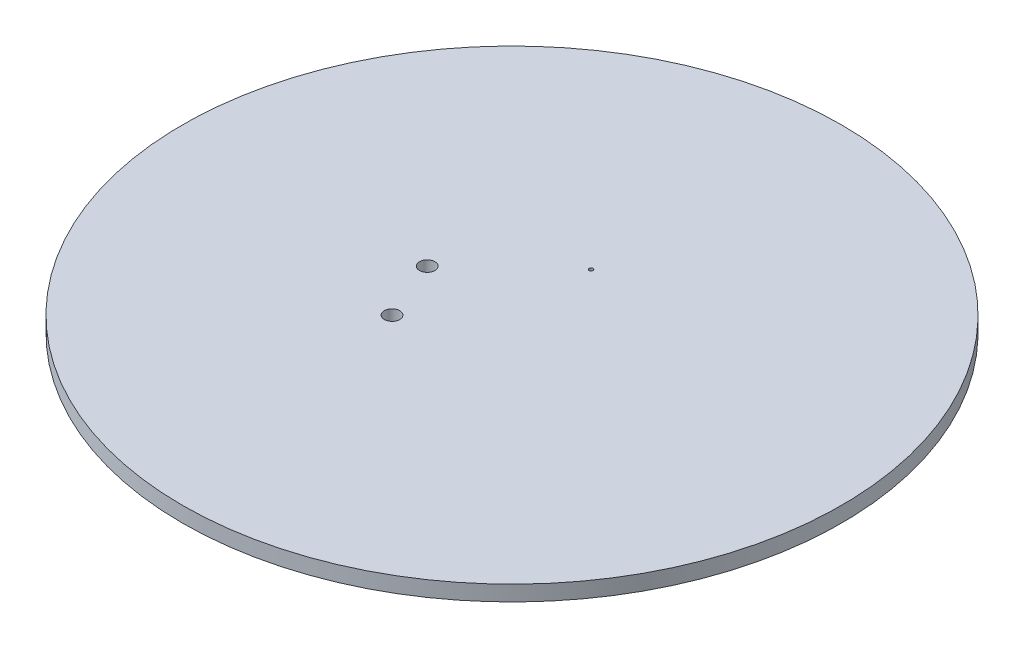
SolidWorks part; units mm, degrees
material "PTFE (general)"
ref_plane "Front Plane" through (0, 0, 0) normal (0, 0, 1) x (1, 0, 0)
ref_plane "Top Plane" through (0, 0, 0) normal (0, 1, 0) x (1, 0, 0)
ref_plane "Right Plane" through (0, 0, 0) normal (1, 0, 0) x (0, 0, -1)
sketch "Sketch1" plane through (0, 0, 0) normal (0, 1, 0) x (1, 0, 0)
  circle A0 centre (0, 0) radius 42.73
  dimension "D2" = 85.46
extrude "Boss-Extrude1" add sketch "Sketch1" along normal blind 2
sketch "Sketch2" plane through (0, 2, 0) normal (0, 1, 0) x (1, 0, 0)
  circle A0 centre (0, 10.25) radius 0.25
  dimension "D1" = 0.5
  dimension "D2" = 10.25
extrude "Cut-Extrude1" cut sketch "Sketch2" against normal through all both and the other way through all
sketch "Sketch3" plane through (0, 2, 0) normal (0, 1, 0) x (1, 0, 0)
  line L0 (0, 0) -> (-36.0536, 0) construction
  line L1 (0, 0) -> (0, 10.25) construction
  line L2 (0, 10.25) -> (0, 0) construction
  line L3 (0, 0) -> (-21.4265, -21.4265) construction
  circle A0 centre (-11, 0) radius 1
  circle A1 centre (-7.7782, -7.7782) radius 1
  dimension "D1" = 2
  dimension "D3" = 2
  dimension "D2" = 11
  dimension "D4" = 11
extrude "Cut-Extrude2" cut sketch "Sketch3" against normal through all both and the other way through all
